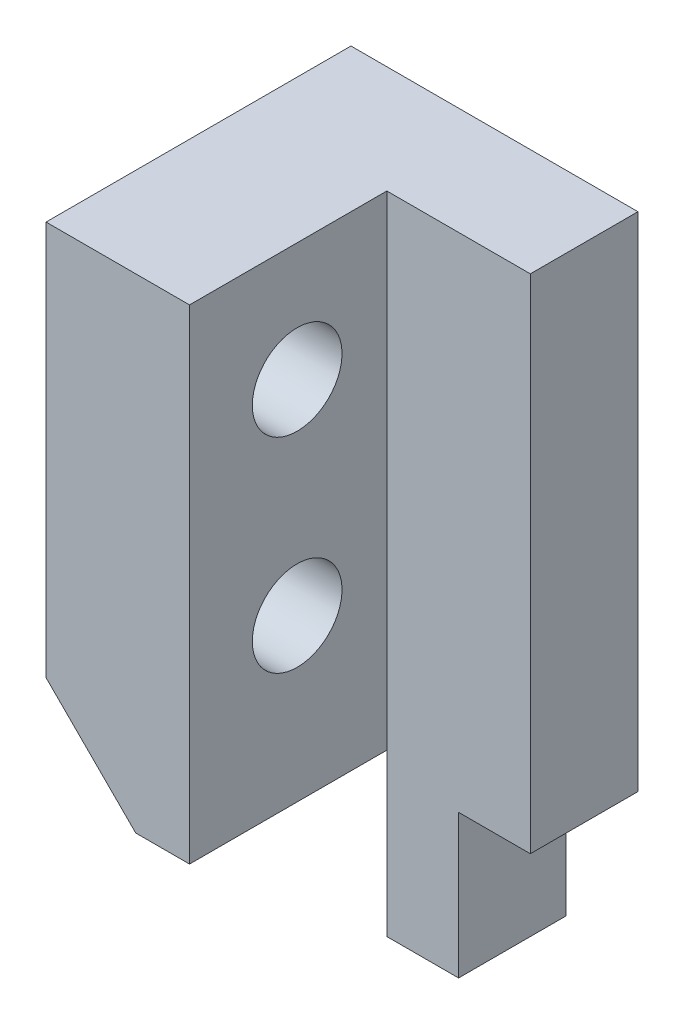
SolidWorks part; units mm, degrees
material "SKD11淬火HRC56-60"
ref_plane "前基準面" through (0, 0, 0) normal (0, 0, 1) x (1, 0, 0)
ref_plane "上基準面" through (0, 0, 0) normal (0, 1, 0) x (1, 0, 0)
ref_plane "右基準面" through (0, 0, 0) normal (1, 0, 0) x (0, 0, -1)
sketch "草图1" plane through (0, 0, 0) normal (0, 0, 1) x (1, 0, 0)
  line L1 (0, 0) -> (8, 0)
  line L2 (0, 0) -> (0, 18)
  line L3 (0, 18) -> (8, 18)
  line L4 (8, 0) -> (8, 18)
  dimension "D1" = 8
  dimension "D2" = 18
extrude "凸台-拉伸1" add sketch "草图1" along normal blind 8.5
sketch "草图2" plane through (0, 18, 0) normal (0, 1, 0) x (1, 0, 0)
  line L1 (8, -8.5) -> (4, -8.5)
  line L2 (8, -8.5) -> (8, -3)
  line L3 (8, -3) -> (4, -3)
  line L4 (4, -8.5) -> (4, -3)
  dimension "D1" = 4
  dimension "D2" = 5.5
extrude "切除-拉伸1" cut sketch "草图2" against normal through all
hole_wizard "M3 螺纹孔1" positions "草图4" profile "草图3" tap size "M3" standard "ISO" end condition through all
sketch "草图4" plane through (0, 0, 0) normal (-1, 0, 0) x (0, 0, 1)
  line L0 (8.5, 18) -> (0, 18) construction
  line L1 (8.5, 18) -> (8.5, 0) construction
  point P0 (5.5, 14.7)
  point P1 (5.5, 9)
  dimension "D1" = 5.7
  dimension "D2" = 3.3
  dimension "D3" = 3
sketch "草图3" plane through (0, 14.7, 5.5) normal (0, 1, 0) x (0, 0, 1)
  line L0 (0, 0) -> (0, 8)
  line L1 (0, 8) -> (1.25, 8)
  line L2 (1.25, 8) -> (1.25, 0)
  line L5 (1.25, 0) -> (0, 0)
  line L11 (0, -6.35) -> (0, 107.95) construction
  dimension "通孔螺纹孔钻头直径" = 2.5
  dimension "通孔螺纹孔钻头深度" = 8
cosmetic thread "孔螺蚊线1" parameters "D2"=3
cosmetic thread "孔螺蚊线2" parameters "D2"=3
sketch "草图5" plane through (4, 0, 0) normal (1, 0, 0) x (0, 0, -1)
  line L0 (-8.5, 0) -> (-8.5, 18) construction
  line L1 (-3, 0) -> (-8.5, 0)
  line L2 (-3, 0) -> (-3, 4)
  line L3 (-3, 4) -> (-8.5, 4)
  line L4 (-8.5, 0) -> (-8.5, 4)
  dimension "D1" = 4
extrude "切除-拉伸2" cut sketch "草图5" against normal blind 8.5
sketch "草图6" plane through (0, 0, 3) normal (0, 0, 1) x (1, 0, 0)
  line L1 (8, 0) -> (6, 0)
  line L2 (8, 0) -> (8, 4)
  line L3 (8, 4) -> (6, 4)
  line L4 (6, 0) -> (6, 4)
  dimension "D1" = 2
  dimension "D2" = 4
extrude "切除-拉伸3" cut sketch "草图6" against normal through all
sketch "草图7" plane through (0, 0, 0) normal (0, 0, -1) x (-1, 0, 0)
  line L0 (-6, 4) -> (-6, 0) construction
  line L1 (0, 0) -> (-4, 0)
  line L2 (0, 0) -> (0, 4.5)
  line L3 (0, 4.5) -> (-4, 4.5)
  line L4 (-4, 0) -> (-4, 4.5)
  dimension "D1" = 2
  dimension "D2" = 4.5
extrude "切除-拉伸4" cut sketch "草图7" against normal through all
chamfer "倒角1" distance 2.5 angle 45 1 edges at (0, 4.5, 4.25)
